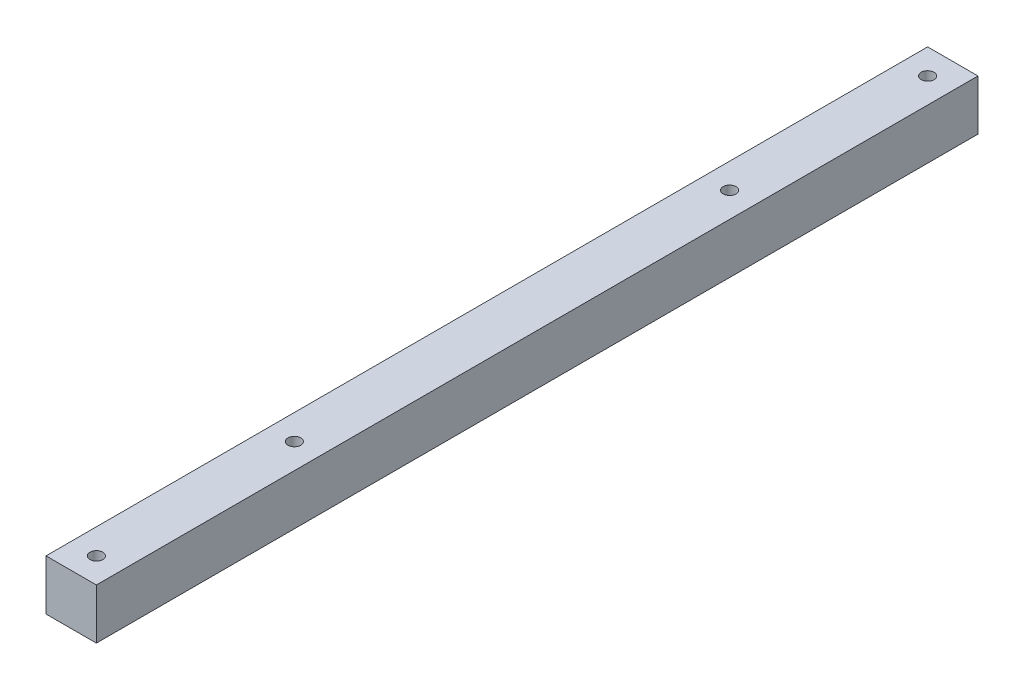
SolidWorks part; units mm, degrees
ref_plane "Front" through (0, 0, 0) normal (0, 0, 1) x (1, 0, 0)
ref_plane "Top" through (0, 0, 0) normal (0, 1, 0) x (1, 0, 0)
ref_plane "Right" through (0, 0, 0) normal (1, 0, 0) x (0, 0, -1)
sketch "草图1" plane through (0, 0, 0) normal (0, 0, 1) x (1, 0, 0)
  line L1 (0, 0) -> (20, 0)
  line L2 (0, 0) -> (0, -20)
  line L3 (0, -20) -> (20, -20)
  line L4 (20, 0) -> (20, -20)
extrude "凸台-拉伸1" add sketch "草图1" along normal blind 350
sketch "草图2" plane through (0, 0, 0) normal (0, 1, 0) x (1, 0, 0)
  line L0 (0, -350) -> (0, 0) construction
  line L1 (20, -350) -> (0, -350) construction
  line L2 (20, 0) -> (0, 0) construction
  line L3 (20, -350) -> (20, 0) construction
  circle A0 centre (10, -340) radius 2.55
  circle A1 centre (10, -10) radius 2.55
  circle A2 centre (10, -261.4) radius 2.55
  circle A3 centre (10, -88.6) radius 2.55
  point P16 (0, 0)
  dimension "D1" = 5.1
  dimension "D2" = 5.1
  dimension "D7" = 78.6
  dimension "D3" = 10
  dimension "D4" = 10
  dimension "D5" = 10
  dimension "D6" = 10
  dimension "D8" = 78.6
extrude "切除-拉伸1" cut sketch "草图2" against normal blind 79
